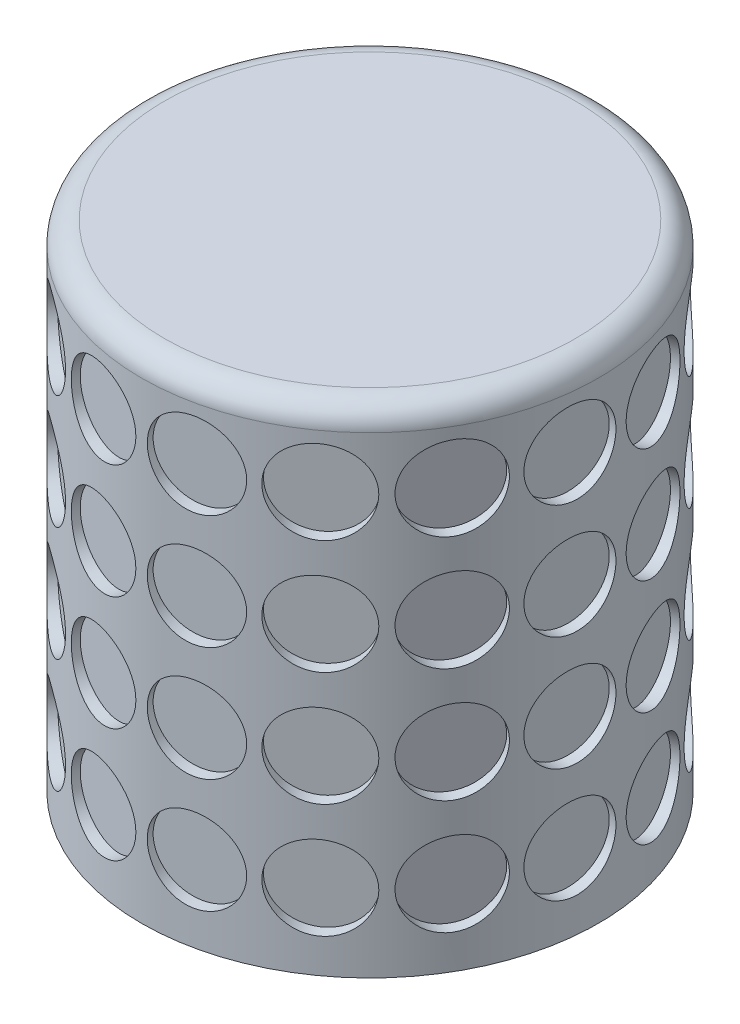
SolidWorks part; units mm, degrees
ref_plane "Plan de face" through (0, 0, 0) normal (1, 0, 0) x (0, 1, 0)
ref_plane "Plan de dessus" through (0, 0, 0) normal (0, 0, 1) x (0, 1, 0)
ref_plane "Plan de droite" through (0, 0, 0) normal (0, 1, 0) x (-1, 0, 0)
sketch "Esquisse1" plane through (0, 0, 0) normal (0, 0, 1) x (0, 1, 0)
  line L0 (56.3846, 24.5) -> (3.2137, 24.5) construction
  line L1 (-8.6154, 54.5) -> (46.3846, 54.5)
  line L2 (-8.6154, 54.5) -> (-8.6154, 47)
  line L3 (-8.6154, 47) -> (46.3846, 47)
  line L4 (46.3846, 54.5) -> (46.3846, 47)
  line L5 (46.3846, 54.5) -> (56.3846, 54.5)
  line L6 (46.3846, 54.5) -> (46.3846, -5.5)
  line L7 (46.3846, -5.5) -> (56.3846, -5.5)
  line L8 (56.3846, 54.5) -> (56.3846, -5.5)
  line L9 (46.3846, -5.5) -> (-8.6154, -5.5)
  line L10 (46.3846, -5.5) -> (46.3846, 2)
  line L11 (46.3846, 2) -> (-8.6154, 2)
  line L12 (-8.6154, -5.5) -> (-8.6154, 2)
  dimension "D1" = 10
  dimension "D2" = 7.5
  dimension "D3" = 7.5
  dimension "D4" = 45
  dimension "D5" = 55
  dimension "D6" = 55
revolve "Révolution1" add sketch "Esquisse1" angle 360 about L0
sketch "Esquisse3" plane through (0, 56.3846, 0) normal (0, 1, 0) x (-1, 0, 0)
  line L0 (24.5, 0) -> (24.5, -30)
  line L1 (24.5, 0) -> (29.7094, -29.5442)
  circle A0 centre (24.5, 0) radius 30 construction
  dimension "D1" = 10
ref_plane "Plan1" through (-24.5, 56.3846, -30) normal (0, 0, -1) x (-1, 0, 0)
fillet "Congé1" radius 3 1 edges at (-24.5, 56.3846, 30)
sketch "Esquisse4" plane through (-24.5, 56.3846, -30) normal (0, 0, -1) x (-1, 0, 0)
  line L0 (-30, -65) -> (30, -65) construction
  circle A0 centre (0, -10) radius 5.5
  circle A1 centre (0, -25) radius 5.5
  circle A2 centre (0, -40) radius 5.5
  circle A3 centre (0, -55) radius 5.5
  dimension "D1" = 11
  dimension "D2" = 11
  dimension "D3" = 11
  dimension "D4" = 11
  dimension "D5" = 15
  dimension "D6" = 15
  dimension "D7" = 0
  dimension "D8" = 15
  dimension "D9" = 10
  dimension "D10" = 0
  dimension "D11" = 0
  dimension "D12" = 0
extrude "Enlèv. mat.-Extru.1" cut sketch "Esquisse4" against normal blind 1.5
pattern_circular "Répétition circulaire1" count 15 every 24 about axis through (-24.5, 0, 0) along (0, 1, 0) of "Enlèv. mat.-Extru.1"
sketch "Esquisse5" plane through (0, 46.3846, 0) normal (0, -1, 0) x (1, 0, 0)
  circle A0 centre (-24.5, 0) radius 6.5
  circle A1 centre (-24.5, 0) radius 4.75
  dimension "D1" = 9.5
  dimension "D2" = 13
extrude "Boss.-Extru.1" add sketch "Esquisse5" along normal blind 20
fillet "Congé2" radius 10 1 edges at (-24.5, 46.3846, 6.5)
